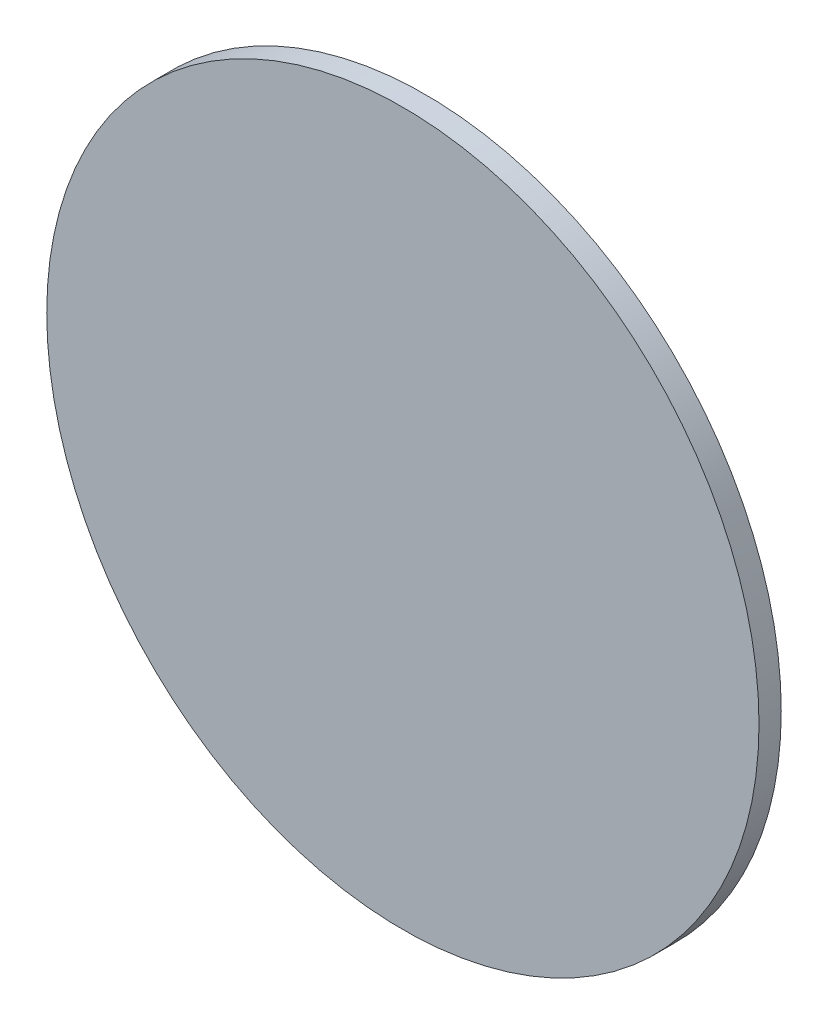
SolidWorks part; units mm, degrees
material "Thornel Mat VMA"
ref_plane "Front Plane" through (0, 0, 0) normal (0, 0, 1) x (1, 0, 0)
ref_plane "Top Plane" through (0, 0, 0) normal (0, 1, 0) x (1, 0, 0)
ref_plane "Right Plane" through (0, 0, 0) normal (1, 0, 0) x (0, 0, -1)
sketch "Sketch1" plane through (0, 0, 0) normal (0, 0, 1) x (1, 0, 0)
  circle A0 centre (0, 0) radius 50.8
  dimension "D1" = 101.6
extrude "Boss-Extrude1" add sketch "Sketch1" along normal blind 3.175
